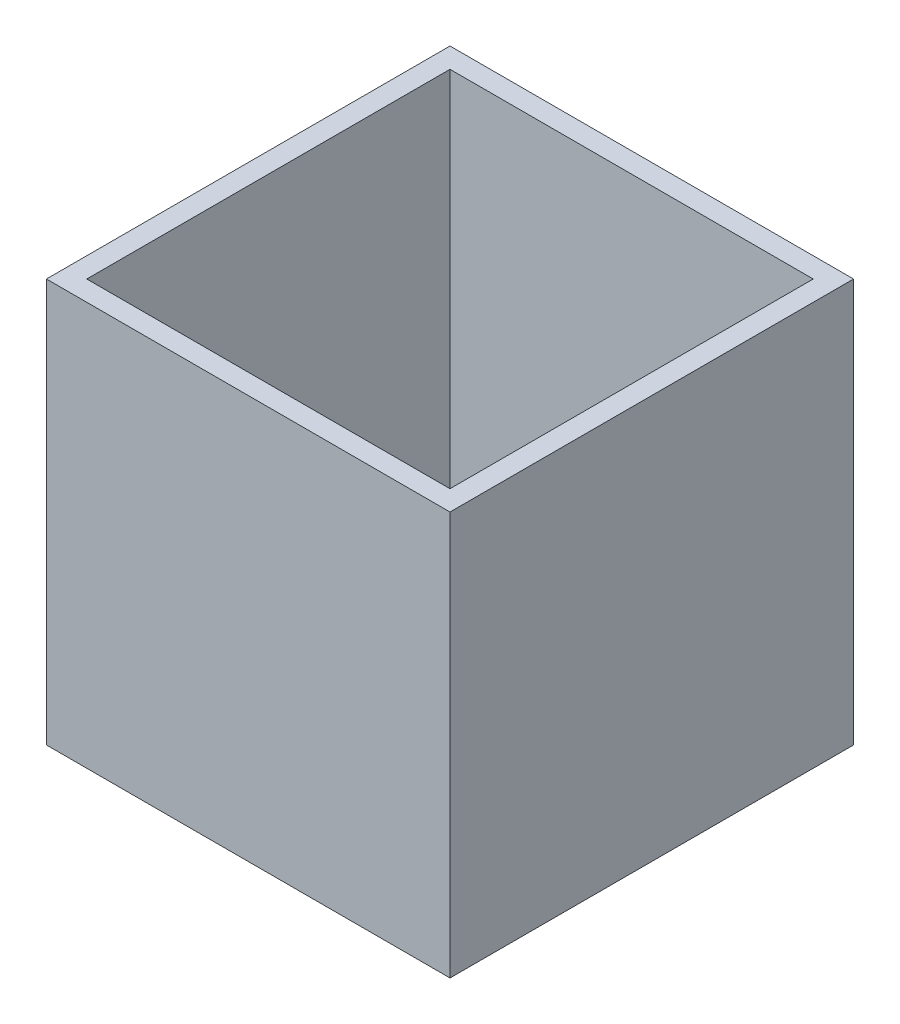
SolidWorks part; units mm, degrees
material "Polyurethane Foam Rigid"
ref_plane "Front Plane" through (0, 0, 0) normal (0, 0, 1) x (1, 0, 0)
ref_plane "Top Plane" through (0, 0, 0) normal (0, 1, 0) x (1, 0, 0)
ref_plane "Right Plane" through (0, 0, 0) normal (1, 0, 0) x (0, 0, -1)
sketch "Sketch2" plane through (0, 0, 0) normal (0, 1, 0) x (1, 0, 0)
  line L1 (-50, 50) -> (50, 50)
  line L2 (-50, 50) -> (-50, -50)
  line L3 (-50, -50) -> (50, -50)
  line L4 (50, 50) -> (50, -50)
  dimension "D1" = 100
  dimension "D2" = 100
  dimension "D3" = 50
  dimension "D4" = 50
extrude "Boss-Extrude1" add sketch "Sketch2" along normal blind 100
shell "Shell1" thickness 5
